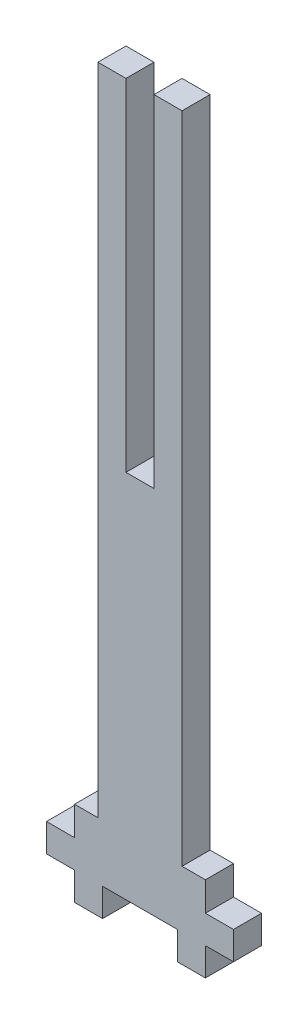
SolidWorks part; units mm, degrees
ref_plane "Front Plane" through (0, 0, 0) normal (0, 0, 1) x (1, 0, 0)
ref_plane "Top Plane" through (0, 0, 0) normal (0, 1, 0) x (1, 0, 0)
ref_plane "Right Plane" through (0, 0, 0) normal (1, 0, 0) x (0, 0, -1)
sketch "스케치1" plane through (0, 0, 0) normal (0, 0, 1) x (1, 0, 0)
  line L0 (0, 0) -> (0, -33.446) construction
  line L1 (-7, -39.546) -> (7, -39.546) construction
  line L2 (-7, -39.546) -> (-7, 39.546) construction
  line L3 (-7, 39.546) -> (7, 39.546) construction
  line L4 (7, -39.546) -> (7, 39.546) construction
  line L5 (-7, -39.546) -> (7, 39.546) construction
  line L6 (-7, 39.546) -> (7, -39.546) construction
  line L7 (-4, -39.546) -> (4, -39.546) construction
  line L8 (-4, -39.546) -> (-4, -33.446)
  line L9 (-4, -33.446) -> (4, -33.446)
  line L10 (4, -39.546) -> (4, -33.446)
  line L11 (-4, -39.546) -> (4, -33.446) construction
  line L12 (-4, -33.446) -> (4, -39.546) construction
  line L13 (4.5, -30.446) -> (-4.5, -30.446) construction
  line L14 (7, -30.446) -> (4.5, -30.446)
  line L15 (7, -30.446) -> (7, 39.546) construction
  line L16 (7, 39.546) -> (4.5, 39.546) construction
  line L17 (4.5, -30.446) -> (4.5, 39.546) construction
  line L18 (7, -30.446) -> (4.5, 39.546) construction
  line L19 (7, 39.546) -> (4.5, -30.446) construction
  line L20 (-4.5, 39.546) -> (-7, 39.546) construction
  line L21 (-4.5, 39.546) -> (-4.5, -30.446) construction
  line L22 (-4.5, -30.446) -> (-7, -30.446)
  line L23 (-7, 39.546) -> (-7, -30.446) construction
  line L24 (-4.5, 39.546) -> (-7, -30.446) construction
  line L25 (-4.5, -30.446) -> (-7, 39.546) construction
  line L26 (4, -39.546) -> (7, -39.546)
  line L27 (-1.5, 30.446) -> (1.5, 30.446) construction
  line L28 (-1.5, 30.446) -> (-1.5, -30.446) construction
  line L29 (-1.5, -30.446) -> (1.5, -30.446) construction
  line L30 (1.5, 30.446) -> (1.5, -30.446) construction
  line L31 (-1.5, 30.446) -> (1.5, -30.446) construction
  line L32 (-1.5, -30.446) -> (1.5, 30.446) construction
  line L33 (7, -39.546) -> (7, -30.446)
  line L34 (-7, -30.446) -> (-7, -39.546)
  line L35 (-7, -39.546) -> (-4, -39.546)
  line L36 (-4.5, 39.546) -> (-7, 39.546) construction
  line L37 (-7, 39.546) -> (-7, -39.546)
  line L38 (4.5, 39.546) -> (7, 39.546) construction
  line L39 (-4.5, -30.446) -> (-4.5, 39.546)
  line L40 (4.5, 39.546) -> (4.5, -30.446)
  line L41 (-4.5, 39.546) -> (4.5, 39.546)
  point P0 (0, 0)
  point P10 (0, -36.496)
  point P16 (5.75, 4.55)
  point P20 (-5.75, 4.55)
  dimension "D1" = 69.992
  dimension "D2" = 3
  dimension "D3" = 8
  dimension "D4" = 6.1
  dimension "D5" = 3
  dimension "D6" = 3
  dimension "D7" = 3
extrude "보스-돌출1" add sketch "스케치1" along normal blind 3 contours L41 L39 L22 L34 L35 L8 L9 L10 L26 L33 L14 L40
sketch "스케치2" plane through (0, 0, 3) normal (0, 0, 1) x (1, 0, 0)
  line L0 (0, 39.546) -> (0, -33.446) construction
  line L1 (-4.5, 39.546) -> (4.5, 39.546) construction
  line L2 (-4, -33.446) -> (4, -33.446) construction
  line L4 (-1.5, 39.546) -> (1.5, 39.546)
  line L5 (-1.5, 39.546) -> (-1.5, 3.05)
  line L6 (-1.5, 3.05) -> (1.5, 3.05)
  line L7 (1.5, 39.546) -> (1.5, 3.05)
  line L8 (-1.5, 39.546) -> (1.5, 3.05) construction
  line L9 (-1.5, 3.05) -> (1.5, 39.546) construction
  point P6 (0, 3.05)
  point P7 (0, 21.298)
  dimension "D1" = 3
extrude "컷-돌출1" cut sketch "스케치2" against normal up to surface (3 mm away) up to face at (0, -22.314, 0)
sketch "스케치3" plane through (0, 0, 3) normal (0, 0, 1) x (1, 0, 0)
  line L0 (-7, -39.546) -> (-4, -39.546) construction
  line L1 (-7, -36.546) -> (-10, -36.546)
  line L2 (-7, -36.546) -> (-7, -33.546)
  line L3 (-7, -33.546) -> (-10, -33.546)
  line L4 (-10, -36.546) -> (-10, -33.546)
  line L5 (-7, -36.546) -> (-10, -33.546) construction
  line L6 (-7, -33.546) -> (-10, -36.546) construction
  line L7 (7, -36.546) -> (10, -36.546)
  line L8 (7, -36.546) -> (7, -33.546)
  line L9 (7, -33.546) -> (10, -33.546)
  line L10 (10, -36.546) -> (10, -33.546)
  line L11 (7, -36.546) -> (10, -33.546) construction
  line L12 (7, -33.546) -> (10, -36.546) construction
  line L13 (7, -39.546) -> (7, -30.446) construction
  line L14 (-7, -30.446) -> (-7, -39.546) construction
  point P4 (-8.5, -35.046)
  point P10 (8.5, -35.046)
  dimension "D1" = 3
  dimension "D2" = 3
  dimension "D3" = 3
  dimension "D4" = 3
  dimension "D5" = 3
  dimension "D6" = 3
extrude "보스-돌출2" add sketch "스케치3" against normal blind 3
sketch "스케치4" plane through (0, 0, 3) normal (0, 0, 1) x (1, 0, 0)
  line L0 (4, -39.546) -> (4, -33.446) construction
  line L1 (-4, -33.446) -> (4, -33.446)
  line L2 (-4, -33.446) -> (-4, -36.546)
  line L3 (-4, -36.546) -> (4, -36.546)
  line L4 (4, -33.446) -> (4, -36.546)
  line L5 (-4, -33.446) -> (4, -36.546) construction
  line L6 (-4, -36.546) -> (4, -33.446) construction
  line L7 (4, -36.546) -> (7, -36.546) construction
  point P4 (0, -34.996)
extrude "보스-돌출3" add sketch "스케치4" against normal blind 3
